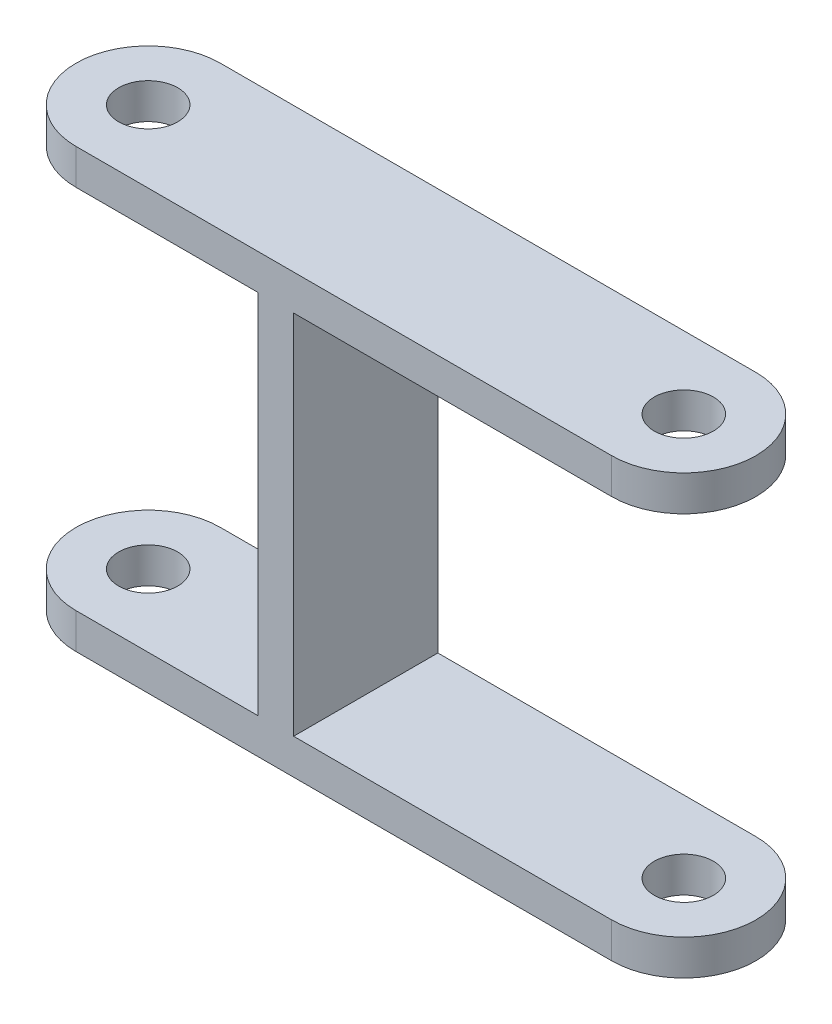
SolidWorks part; units mm, degrees
ref_plane "Front Plane" through (0, 0, 0) normal (0, 0, 1) x (1, 0, 0)
ref_plane "Top Plane" through (0, 0, 0) normal (0, 1, 0) x (1, 0, 0)
ref_plane "Right Plane" through (0, 0, 0) normal (1, 0, 0) x (0, 0, -1)
sketch "Sketch7" plane through (0, 0, 0) normal (0, 1, 0) x (1, 0, 0)
  line L0 (13.7299, 49.1695) -> (59.0299, 49.1695) construction
  line L1 (13.7299, 55.2695) -> (59.0299, 55.2695)
  line L2 (13.7299, 43.0695) -> (59.0299, 43.0695)
  arc A0 (13.7299, 55.2695) -> (13.7299, 43.0695) centre (13.7299, 49.1695) ccw
  arc A1 (59.0299, 43.0695) -> (59.0299, 55.2695) centre (59.0299, 49.1695) ccw
  circle A2 centre (13.7299, 49.1695) radius 2.5
  circle A3 centre (59.0299, 49.1695) radius 2.5
  point P2 (36.3799, 49.1695)
  dimension "D1" = 6.1
  dimension "D3" = 5
  dimension "D2" = 45.3
extrude "Boss-Extrude3" add sketch "Sketch7" along normal blind 37
sketch "Sketch8" plane through (0, 0, -55.2695) normal (0, 0, -1) x (-1, 0, 0)
  line L0 (-13.7299, 37) -> (-13.7299, 0) construction
  line L1 (-59.0299, 37) -> (-13.7299, 37)
  line L2 (-59.0299, 37) -> (-59.0299, 34)
  line L3 (-59.0299, 34) -> (-13.7299, 34)
  line L4 (-13.7299, 37) -> (-13.7299, 34)
  line L6 (-59.0299, 0) -> (-13.7299, 0)
  line L7 (-59.0299, 0) -> (-59.0299, 3)
  line L8 (-59.0299, 3) -> (-13.7299, 3)
  line L9 (-13.7299, 0) -> (-13.7299, 3)
  line L10 (-32.1299, 34) -> (-29.1299, 34)
  line L11 (-32.1299, 34) -> (-32.1299, 3)
  line L12 (-32.1299, 3) -> (-29.1299, 3)
  line L13 (-29.1299, 34) -> (-29.1299, 3)
  line L14 (-32.1299, 34) -> (-68.2857, 34)
  line L15 (-32.1299, 34) -> (-32.1299, 3)
  line L16 (-32.1299, 3) -> (-68.2857, 3)
  line L17 (-68.2857, 34) -> (-68.2857, 3)
  line L18 (-29.1299, 34) -> (-5.7196, 34)
  line L19 (-29.1299, 34) -> (-29.1299, 3)
  line L20 (-29.1299, 3) -> (-5.7196, 3)
  line L21 (-5.7196, 34) -> (-5.7196, 3)
  point P12 (-32.1299, 34)
  line M19 (-13.7299, 0) -> (-13.7299, 37)
  dimension "D1" = 3
  dimension "D2" = 3
  dimension "D3" = 26.9
  dimension "D4" = 3
extrude "Cut-Extrude4" cut sketch "Sketch8" against normal through all contours L3 L13 L8 M19 | L21 L18 L20 M19 | L15 L14 L17 L16
